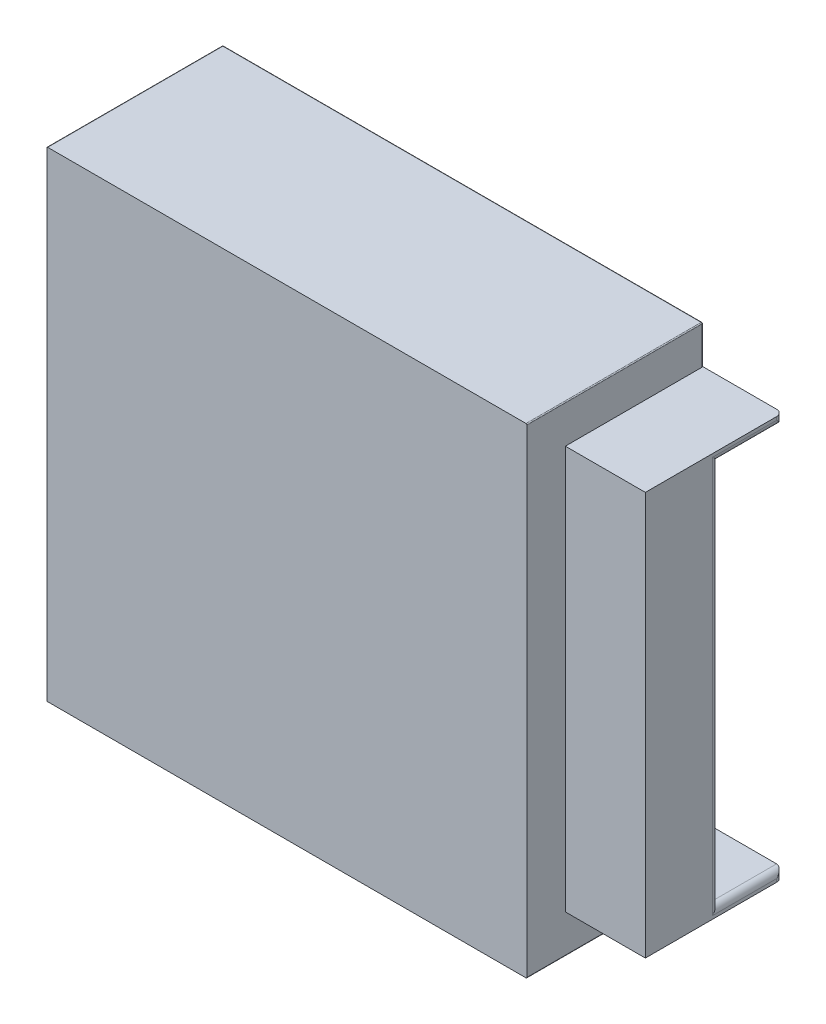
SolidWorks part; units mm, degrees
other "标注1"
sketch "草图9" plane through (0, -150, 0) normal (-0.0709, -0.2266, -0.9714) x (-0.9769, 0.2128, 0.0217)
ref_plane "前视基准面" through (0, 0, 0) normal (0, 0, 1) x (1, 0, 0)
ref_plane "上视基准面" through (0, 0, 0) normal (0, 1, 0) x (1, 0, 0)
ref_plane "右视基准面" through (0, 0, 0) normal (1, 0, 0) x (0, 0, -1)
sketch "草图1" plane through (0, 0, 0) normal (0, 0, 1) x (1, 0, 0)
  line L1 (0, 0) -> (150, 0)
  line L2 (0, 0) -> (0, -150)
  line L3 (0, -150) -> (150, -150)
  line L4 (150, 0) -> (150, -150)
  dimension "D1" = 150
  dimension "D2" = 150
extrude "凸台-拉伸2" add sketch "草图1" along normal blind 55
sketch "草图2" plane through (0, 0, 0) normal (0, 0, -1) x (-1, 0, 0)
  line L0 (0, -75) -> (-180.3535, -75) construction
  line L1 (-75, -150) -> (-75, 0) construction
  line L2 (-97, -55.8097) -> (-92.6, -55.8097) construction
  line L3 (-97, -53) -> (-53, -53)
  line L4 (0, -150) -> (0, 0)
  line L5 (0, 0) -> (-150, 0)
  line L6 (-150, 0) -> (-150, -150)
  line L7 (-150, -150) -> (0, -150)
  line L8 (0, -150) -> (0, 0)
  line L9 (0, 0) -> (-150, 0)
  line L10 (-150, 0) -> (-150, -150)
  line L11 (-150, -150) -> (0, -150)
  line L12 (-97, -53) -> (-97, -97)
  line L13 (-97, -97) -> (-53, -97)
  line L14 (-53, -53) -> (-53, -97)
  line L15 (-97, -53) -> (-53, -97) construction
  line L16 (-97, -97) -> (-53, -53) construction
  line L17 (-92.6, -53) -> (-97, -57.4)
  line L18 (-57.4, -53) -> (-53, -57.4)
  line L19 (-57.4, -97) -> (-53, -92.6)
  line L20 (-92.6, -97) -> (-97, -92.6)
  point P8 (-75, -75)
  dimension "D2" = 44
  dimension "D3" = 44
  dimension "D4" = 4.4
  dimension "D5" = 4.4
  dimension "D6" = 4.4
  dimension "D1" = 0
extrude "切除-拉伸1" cut sketch "草图2" against normal blind 52 contours L20 L13 L19 L14 L18 L3 L17 L12
sketch "草图3" plane through (0, 0, 0) normal (0, 0, -1) x (-1, 0, 0)
  line L0 (-53, -62.4) -> (-33, -62.4)
  line L1 (-53, -57.4) -> (-53, -92.6) construction
  line L2 (-33, -62.4) -> (-33, -87.6)
  line L3 (-33, -87.6) -> (-53, -87.6)
  line L4 (0, -150) -> (0, 0)
  line L5 (0, 0) -> (-150, 0)
  line L6 (-150, 0) -> (-150, -150)
  line L7 (-150, -150) -> (0, -150)
  line L8 (0, -150) -> (0, 0)
  line L9 (0, 0) -> (-150, 0)
  line L10 (-150, 0) -> (-150, -150)
  line L11 (-150, -150) -> (0, -150)
  line L12 (-53, -57.4) -> (-53, -92.6) construction
  line M16 (-53, -57.4) -> (-53, -92.6)
  dimension "D2" = 5
  dimension "D3" = 5
  dimension "D4" = 20
  dimension "D1" = 0
extrude "切除-拉伸2" cut sketch "草图3" against normal blind 52 contours L3 L2 L0 M16
sketch "草图4" plane through (0, 0, 0) normal (0, 0, -1) x (-1, 0, 0)
  line L4 (-90.6, -53) -> (-90.6, -29.3365)
  line L5 (-92.6, -53) -> (-57.4, -53) construction
  line L6 (-59.4, -53) -> (-59.4, -29.3365)
  line L7 (-59.4, -29.3365) -> (-90.6, -29.3365)
  line L8 (0, -150) -> (0, 0)
  line L9 (0, 0) -> (-150, 0)
  line L10 (-150, 0) -> (-150, -150)
  line L11 (-150, -150) -> (0, -150)
  line L12 (0, -150) -> (0, 0)
  line L13 (0, 0) -> (-150, 0)
  line L14 (-150, 0) -> (-150, -150)
  line L15 (-150, -150) -> (0, -150)
  line M17 (-92.6, -53) -> (-57.4, -53)
  dimension "D2" = 23.6635
  dimension "D3" = 2
  dimension "D4" = 2
  dimension "D1" = 0
extrude "切除-拉伸3" cut sketch "草图4" against normal blind 52 contours L6 L7 L4 M17
sketch "草图5" plane through (0, 0, 0) normal (0, 0, -1) x (-1, 0, 0)
  line L0 (-119.1643, -135) -> (-119.1643, -150) construction
  line L1 (-121.7237, 0) -> (-121.7237, -15) construction
  line L2 (-97, -60.4735) -> (-104, -60.4735) construction
  line L3 (-97, -57.4) -> (-97, -92.6) construction
  line L4 (0, -150) -> (0, 0)
  line L5 (0, 0) -> (-150, 0)
  line L6 (-150, 0) -> (-150, -150)
  line L7 (-150, -150) -> (0, -150)
  line L8 (0, -150) -> (0, 0)
  line L9 (0, 0) -> (-150, 0)
  line L10 (-150, 0) -> (-150, -150)
  line L11 (-150, -150) -> (0, -150)
  line L12 (-104, -60.4735) -> (-104, 3.8558) construction
  line L13 (-104, -60.4735) -> (-104, -150) construction
  line L14 (-121.7237, -15) -> (-88.1368, -15) construction
  line L16 (-104, -15) -> (-179, -15)
  line L17 (-104, -15) -> (-104, -135)
  line L18 (-104, -135) -> (-179, -135)
  line L19 (-179, -15) -> (-179, -135)
  dimension "D2" = 15
  dimension "D3" = 7
  dimension "D4" = 15
  dimension "D5" = 75
  dimension "D1" = 0
extrude "切除-拉伸4" cut sketch "草图5" against normal blind 40 contours L18 L17 L16 L10 | L16 L19 L18 L10
sketch "草图6" plane through (150, 0, 0) normal (1, 0, 0) x (0, 0, -1)
  line L1 (-40, -15) -> (-43, -15)
  line L2 (-40, -15) -> (-40, -135)
  line L3 (-40, -135) -> (-43, -135)
  line L4 (-43, -15) -> (-43, -135)
  line L5 (0, -135) -> (-43, -135)
  line L6 (0, -135) -> (0, -138)
  line L7 (0, -138) -> (-43, -138)
  line L8 (0, -135) -> (-40, -135)
  line L9 (-40, -135) -> (-40, -15)
  line L10 (-40, -15) -> (0, -15)
  line L11 (0, -15) -> (0, 0)
  line L12 (0, 0) -> (-55, 0)
  line L13 (-55, 0) -> (-55, -150)
  line L14 (-55, -150) -> (0, -150)
  line L15 (0, -150) -> (0, -135)
  line L16 (0, -135) -> (-40, -135)
  line L17 (-40, -135) -> (-40, -15)
  line L18 (-40, -15) -> (0, -15)
  line L19 (0, -15) -> (0, 0)
  line L20 (0, 0) -> (-55, 0)
  line L21 (-55, 0) -> (-55, -150)
  line L22 (-55, -150) -> (0, -150)
  line L23 (0, -150) -> (0, -135)
  line L24 (-43, -135) -> (-43, -138)
  line L25 (-43, -15) -> (0, -15)
  line L26 (-43, -15) -> (-43, -12)
  line L27 (-43, -12) -> (0, -12)
  line L28 (0, -15) -> (0, -12)
  line M10 (0, -135) -> (-40, -135)
  line M11 (-40, -135) -> (-40, -15)
  line M12 (-40, -15) -> (0, -15)
  line M13 (0, -15) -> (0, 0)
  line M17 (0, -150) -> (0, -135)
  dimension "D2" = 3
  dimension "D3" = 3
  dimension "D4" = 3
  dimension "D1" = 0
extrude "凸台-拉伸4" add sketch "草图6" along normal blind 25 contours L27 L26 L1 M12 M13 | L1 L4 L3 M11 | L3 L24 L7 M17 M10
sketch "草图7" plane through (0, 0, 40) normal (0, 0, -1) x (-1, 0, 0)
  line L1 (-175, -15) -> (-172, -15)
  line L2 (-175, -15) -> (-175, -135)
  line L3 (-175, -135) -> (-172, -135)
  line L4 (-104, -15) -> (-175, -15)
  line L5 (-175, -15) -> (-175, -135)
  line L6 (-175, -135) -> (-104, -135)
  line L7 (-104, -135) -> (-104, -15)
  line L8 (-104, -15) -> (-175, -15)
  line L9 (-175, -15) -> (-175, -135)
  line L10 (-175, -135) -> (-104, -135)
  line L11 (-104, -135) -> (-104, -15)
  line L12 (-172, -15) -> (-172, -135)
  line M7 (-104, -15) -> (-175, -15)
  line M8 (-175, -15) -> (-175, -135)
  line M9 (-175, -135) -> (-104, -135)
  dimension "D2" = 3
  dimension "D1" = 0
extrude "凸台-拉伸5" add sketch "草图7" along normal blind 20 contours L12 M7 M8 M9
sketch "草图8" plane through (0, 0, 0) normal (0, 0, -1) x (-1, 0, 0)
  line L1 (-104, -15) -> (-69, -15)
  line L2 (-104, -15) -> (-104, -29.3365)
  line L3 (-104, -29.3365) -> (-69, -29.3365)
  line L4 (-69, -15) -> (-69, -29.3365)
  line L6 (-59.4, -29.3365) -> (-90.6, -29.3365) construction
  line L8 (-150, -12) -> (-175, -12)
  line L9 (-175, -12) -> (-175, -15)
  line L10 (-175, -138) -> (-150, -138)
  line L11 (-150, -138) -> (-150, -150)
  line L12 (-150, -150) -> (0, -150)
  line L13 (0, -150) -> (0, 0)
  line L14 (0, 0) -> (-150, 0)
  line L15 (-150, 0) -> (-150, -12)
  line L16 (-150, -12) -> (-175, -12)
  line L17 (-175, -12) -> (-175, -15)
  line L18 (-175, -138) -> (-150, -138)
  line L19 (-150, -138) -> (-150, -150)
  line L20 (-150, -150) -> (0, -150)
  line L21 (0, -150) -> (0, 0)
  line L22 (0, 0) -> (-150, 0)
  line L23 (-150, 0) -> (-150, -12)
  line L35 (-104, -135) -> (-175, -135)
  line L36 (-104, -135) -> (-175, -135)
  line L37 (-175, -135) -> (-175, -138)
  line L38 (-175, -135) -> (-175, -138)
  line L39 (-175, -15) -> (-104, -15)
  line L40 (-175, -15) -> (-104, -15)
  line L41 (-104, -15) -> (-104, -135)
  line L42 (-104, -15) -> (-104, -135)
  line M16 (-104, -15) -> (-104, -135)
  line M17 (-90.6, -29.3365) -> (-59.4, -29.3365)
  dimension "D2" = 35
  dimension "D1" = 0
extrude "切除-拉伸6" cut sketch "草图8" against normal blind 30 contours L4 L1 L3 M16 M17
fillet "圆角1" radius 7 2 edges at (104, -22.1683, 30) (79.8, -29.3365, 30)
sketch "草图10" plane through (0, 0, 0) normal (0, 0, -1) x (-1, 0, 0)
  line L0 (-92.6, -97) -> (-92.6, -98.5) construction
  line L1 (-92.6, -98.5) -> (-12.6, -98.5) construction
  line L3 (-92.6, -98.5) -> (-12.6, -98.5)
  line L4 (-92.6, -98.5) -> (-92.6, -148.5)
  line L5 (-92.6, -148.5) -> (-12.6, -148.5)
  line L6 (-12.6, -98.5) -> (-12.6, -148.5)
  line L30 (-90.6, -53) -> (-90.6, -29.3365)
  line L31 (-90.6, -29.3365) -> (-104, -29.3365)
  line L32 (-104, -29.3365) -> (-104, -135)
  line L33 (-104, -135) -> (-175, -135)
  line L34 (-175, -135) -> (-175, -138)
  line L35 (-175, -138) -> (-150, -138)
  line L36 (-150, -138) -> (-150, -150)
  line L37 (-150, -150) -> (0, -150)
  line L38 (0, -150) -> (0, 0)
  line L39 (0, 0) -> (-150, 0)
  line L40 (-150, 0) -> (-150, -12)
  line L41 (-150, -12) -> (-175, -12)
  line L42 (-175, -12) -> (-175, -15)
  line L43 (-175, -15) -> (-69, -15)
  line L44 (-69, -15) -> (-69, -29.3365)
  line L45 (-69, -29.3365) -> (-59.4, -29.3365)
  line L46 (-59.4, -29.3365) -> (-59.4, -53)
  line L47 (-59.4, -53) -> (-57.4, -53)
  line L48 (-57.4, -53) -> (-53, -57.4)
  line L49 (-53, -57.4) -> (-53, -62.4)
  line L50 (-53, -62.4) -> (-33, -62.4)
  line L51 (-33, -62.4) -> (-33, -87.6)
  line L52 (-33, -87.6) -> (-53, -87.6)
  line L53 (-53, -87.6) -> (-53, -92.6)
  line L54 (-53, -92.6) -> (-57.4, -97)
  line L55 (-57.4, -97) -> (-92.6, -97)
  line L56 (-92.6, -97) -> (-97, -92.6)
  line L57 (-97, -92.6) -> (-97, -57.4)
  line L58 (-97, -57.4) -> (-92.6, -53)
  line L59 (-92.6, -53) -> (-90.6, -53)
  line L60 (-90.6, -53) -> (-90.6, -29.3365)
  line L61 (-90.6, -29.3365) -> (-104, -29.3365)
  line L62 (-104, -29.3365) -> (-104, -135)
  line L63 (-104, -135) -> (-175, -135)
  line L64 (-175, -135) -> (-175, -138)
  line L65 (-175, -138) -> (-150, -138)
  line L66 (-150, -138) -> (-150, -150)
  line L67 (-150, -150) -> (0, -150)
  line L68 (0, -150) -> (0, 0)
  line L69 (0, 0) -> (-150, 0)
  line L70 (-150, 0) -> (-150, -12)
  line L71 (-150, -12) -> (-175, -12)
  line L72 (-175, -12) -> (-175, -15)
  line L73 (-175, -15) -> (-69, -15)
  line L74 (-69, -15) -> (-69, -29.3365)
  line L75 (-69, -29.3365) -> (-59.4, -29.3365)
  line L76 (-59.4, -29.3365) -> (-59.4, -53)
  line L77 (-59.4, -53) -> (-57.4, -53)
  line L78 (-57.4, -53) -> (-53, -57.4)
  line L79 (-53, -57.4) -> (-53, -62.4)
  line L80 (-53, -62.4) -> (-33, -62.4)
  line L81 (-33, -62.4) -> (-33, -87.6)
  line L82 (-33, -87.6) -> (-53, -87.6)
  line L83 (-53, -87.6) -> (-53, -92.6)
  line L84 (-53, -92.6) -> (-57.4, -97)
  line L85 (-57.4, -97) -> (-92.6, -97)
  line L86 (-92.6, -97) -> (-97, -92.6)
  line L87 (-97, -92.6) -> (-97, -57.4)
  line L88 (-97, -57.4) -> (-92.6, -53)
  line L89 (-92.6, -53) -> (-90.6, -53)
  dimension "D2" = 1.5
  dimension "D3" = 80
  dimension "D4" = 50
  dimension "D5" = 80
  dimension "D1" = 0
extrude "切除-拉伸7" cut sketch "草图10" against normal blind 30 contours L4 L3 L6 L5
sketch "草图11" plane through (0, 0, 0) normal (0, 0, -1) x (-1, 0, 0)
  line L0 (-92.6, -98.5) -> (-92.6, -148.5) construction
  line L1 (-104, -105) -> (-92.6, -105)
  line L2 (-104, -105) -> (-104, -125)
  line L3 (-104, -125) -> (-92.6, -125)
  line L4 (-92.6, -105) -> (-92.6, -125)
  line L30 (-90.6, -53) -> (-90.6, -29.3365)
  line L31 (-90.6, -29.3365) -> (-104, -29.3365)
  line L32 (-104, -29.3365) -> (-104, -135)
  line L33 (-104, -135) -> (-175, -135)
  line L34 (-175, -135) -> (-175, -138)
  line L35 (-175, -138) -> (-150, -138)
  line L36 (-150, -138) -> (-150, -150)
  line L37 (-150, -150) -> (0, -150)
  line L38 (0, -150) -> (0, 0)
  line L39 (0, 0) -> (-150, 0)
  line L40 (-150, 0) -> (-150, -12)
  line L41 (-150, -12) -> (-175, -12)
  line L42 (-175, -12) -> (-175, -15)
  line L43 (-175, -15) -> (-69, -15)
  line L44 (-69, -15) -> (-69, -29.3365)
  line L45 (-69, -29.3365) -> (-59.4, -29.3365)
  line L46 (-59.4, -29.3365) -> (-59.4, -53)
  line L47 (-59.4, -53) -> (-57.4, -53)
  line L48 (-57.4, -53) -> (-53, -57.4)
  line L49 (-53, -57.4) -> (-53, -62.4)
  line L50 (-53, -62.4) -> (-33, -62.4)
  line L51 (-33, -62.4) -> (-33, -87.6)
  line L52 (-33, -87.6) -> (-53, -87.6)
  line L53 (-53, -87.6) -> (-53, -92.6)
  line L54 (-53, -92.6) -> (-57.4, -97)
  line L55 (-57.4, -97) -> (-92.6, -97)
  line L56 (-92.6, -97) -> (-97, -92.6)
  line L57 (-97, -92.6) -> (-97, -57.4)
  line L58 (-97, -57.4) -> (-92.6, -53)
  line L59 (-92.6, -53) -> (-90.6, -53)
  line L60 (-90.6, -53) -> (-90.6, -29.3365)
  line L61 (-90.6, -29.3365) -> (-104, -29.3365)
  line L62 (-104, -29.3365) -> (-104, -135)
  line L63 (-104, -135) -> (-175, -135)
  line L64 (-175, -135) -> (-175, -138)
  line L65 (-175, -138) -> (-150, -138)
  line L66 (-150, -138) -> (-150, -150)
  line L67 (-150, -150) -> (0, -150)
  line L68 (0, -150) -> (0, 0)
  line L69 (0, 0) -> (-150, 0)
  line L70 (-150, 0) -> (-150, -12)
  line L71 (-150, -12) -> (-175, -12)
  line L72 (-175, -12) -> (-175, -15)
  line L73 (-175, -15) -> (-69, -15)
  line L74 (-69, -15) -> (-69, -29.3365)
  line L75 (-69, -29.3365) -> (-59.4, -29.3365)
  line L76 (-59.4, -29.3365) -> (-59.4, -53)
  line L77 (-59.4, -53) -> (-57.4, -53)
  line L78 (-57.4, -53) -> (-53, -57.4)
  line L79 (-53, -57.4) -> (-53, -62.4)
  line L80 (-53, -62.4) -> (-33, -62.4)
  line L81 (-33, -62.4) -> (-33, -87.6)
  line L82 (-33, -87.6) -> (-53, -87.6)
  line L83 (-53, -87.6) -> (-53, -92.6)
  line L84 (-53, -92.6) -> (-57.4, -97)
  line L85 (-57.4, -97) -> (-92.6, -97)
  line L86 (-92.6, -97) -> (-97, -92.6)
  line L87 (-97, -92.6) -> (-97, -57.4)
  line L88 (-97, -57.4) -> (-92.6, -53)
  line L89 (-92.6, -53) -> (-90.6, -53)
  line M35 (-92.6, -148.5) -> (-92.6, -98.5)
  line M39 (-104, -29.3365) -> (-104, -135)
  dimension "D2" = 20
  dimension "D3" = 25
  dimension "D1" = 0
extrude "切除-拉伸8" cut sketch "草图11" against normal blind 30 contours L3 L1 M39 M35
fillet "圆角2" radius 5 1 edges at (104, -115, 30)
fillet "圆角3" radius 2 7 edges at (104, -29.3365, 18.5) (69, -29.3365, 18.5) (90.6, -29.3365, 15) (92.6, -105, 15) (92.6, -125, 15) (104, -125, 17.5) (104, -105, 17.5)
sketch "草图12" plane through (0, 0, 0) normal (0, 0, -1) x (-1, 0, 0)
  line L1 (-12.6, -115) -> (0, -115)
  line L2 (-12.6, -115) -> (-12.6, -135)
  line L3 (-12.6, -135) -> (0, -135)
  line L4 (0, -115) -> (0, -135)
  line L38 (-92.6, -29.3365) -> (-102, -29.3365)
  line L39 (-104, -31.3365) -> (-104, -103)
  line L40 (-102, -105) -> (-94.6, -105)
  line L41 (-92.6, -103) -> (-92.6, -98.5)
  line L42 (-92.6, -98.5) -> (-12.6, -98.5)
  line L43 (-12.6, -98.5) -> (-12.6, -148.5)
  line L44 (-12.6, -148.5) -> (-92.6, -148.5)
  line L45 (-92.6, -148.5) -> (-92.6, -127)
  line L46 (-94.6, -125) -> (-102, -125)
  line L47 (-104, -127) -> (-104, -135)
  line L48 (-104, -135) -> (-175, -135)
  line L49 (-175, -135) -> (-175, -138)
  line L50 (-175, -138) -> (-150, -138)
  line L51 (-150, -138) -> (-150, -150)
  line L52 (-150, -150) -> (0, -150)
  line L53 (0, -150) -> (0, 0)
  line L54 (0, 0) -> (-150, 0)
  line L55 (-150, 0) -> (-150, -12)
  line L56 (-150, -12) -> (-175, -12)
  line L57 (-175, -12) -> (-175, -15)
  line L58 (-175, -15) -> (-69, -15)
  line L59 (-69, -15) -> (-69, -27.3365)
  line L60 (-67, -29.3365) -> (-59.4, -29.3365)
  line L61 (-59.4, -29.3365) -> (-59.4, -53)
  line L62 (-59.4, -53) -> (-57.4, -53)
  line L63 (-57.4, -53) -> (-53, -57.4)
  line L64 (-53, -57.4) -> (-53, -62.4)
  line L65 (-53, -62.4) -> (-33, -62.4)
  line L66 (-33, -62.4) -> (-33, -87.6)
  line L67 (-33, -87.6) -> (-53, -87.6)
  line L68 (-53, -87.6) -> (-53, -92.6)
  line L69 (-53, -92.6) -> (-57.4, -97)
  line L70 (-57.4, -97) -> (-92.6, -97)
  line L71 (-92.6, -97) -> (-97, -92.6)
  line L72 (-97, -92.6) -> (-97, -57.4)
  line L73 (-97, -57.4) -> (-92.6, -53)
  line L74 (-92.6, -53) -> (-90.6, -53)
  line L75 (-90.6, -53) -> (-90.6, -31.3365)
  line L76 (-92.6, -29.3365) -> (-102, -29.3365)
  line L77 (-104, -31.3365) -> (-104, -103)
  line L78 (-102, -105) -> (-94.6, -105)
  line L79 (-92.6, -103) -> (-92.6, -98.5)
  line L80 (-92.6, -98.5) -> (-12.6, -98.5)
  line L81 (-12.6, -98.5) -> (-12.6, -148.5)
  line L82 (-12.6, -148.5) -> (-92.6, -148.5)
  line L83 (-92.6, -148.5) -> (-92.6, -127)
  line L84 (-94.6, -125) -> (-102, -125)
  line L85 (-104, -127) -> (-104, -135)
  line L86 (-104, -135) -> (-175, -135)
  line L87 (-175, -135) -> (-175, -138)
  line L88 (-175, -138) -> (-150, -138)
  line L89 (-150, -138) -> (-150, -150)
  line L90 (-150, -150) -> (0, -150)
  line L91 (0, -150) -> (0, 0)
  line L92 (0, 0) -> (-150, 0)
  line L93 (-150, 0) -> (-150, -12)
  line L94 (-150, -12) -> (-175, -12)
  line L95 (-175, -12) -> (-175, -15)
  line L96 (-175, -15) -> (-69, -15)
  line L97 (-69, -15) -> (-69, -27.3365)
  line L98 (-67, -29.3365) -> (-59.4, -29.3365)
  line L99 (-59.4, -29.3365) -> (-59.4, -53)
  line L100 (-59.4, -53) -> (-57.4, -53)
  line L101 (-57.4, -53) -> (-53, -57.4)
  line L102 (-53, -57.4) -> (-53, -62.4)
  line L103 (-53, -62.4) -> (-33, -62.4)
  line L104 (-33, -62.4) -> (-33, -87.6)
  line L105 (-33, -87.6) -> (-53, -87.6)
  line L106 (-53, -87.6) -> (-53, -92.6)
  line L107 (-53, -92.6) -> (-57.4, -97)
  line L108 (-57.4, -97) -> (-92.6, -97)
  line L109 (-92.6, -97) -> (-97, -92.6)
  line L110 (-97, -92.6) -> (-97, -57.4)
  line L111 (-97, -57.4) -> (-92.6, -53)
  line L112 (-92.6, -53) -> (-90.6, -53)
  line L113 (-90.6, -53) -> (-90.6, -31.3365)
  arc A7 (-102, -29.3365) -> (-104, -31.3365) centre (-102, -31.3365) ccw
  arc A8 (-104, -103) -> (-102, -105) centre (-102, -103) ccw
  arc A9 (-94.6, -105) -> (-92.6, -103) centre (-94.6, -103) ccw
  arc A10 (-92.6, -127) -> (-94.6, -125) centre (-94.6, -127) ccw
  arc A11 (-102, -125) -> (-104, -127) centre (-102, -127) ccw
  arc A12 (-69, -27.3365) -> (-67, -29.3365) centre (-67, -27.3365) ccw
  arc A13 (-90.6, -31.3365) -> (-92.6, -29.3365) centre (-92.6, -31.3365) ccw
  arc A14 (-102, -29.3365) -> (-104, -31.3365) centre (-102, -31.3365) ccw
  arc A15 (-104, -103) -> (-102, -105) centre (-102, -103) ccw
  arc A16 (-94.6, -105) -> (-92.6, -103) centre (-94.6, -103) ccw
  arc A17 (-92.6, -127) -> (-94.6, -125) centre (-94.6, -127) ccw
  arc A18 (-102, -125) -> (-104, -127) centre (-102, -127) ccw
  arc A19 (-69, -27.3365) -> (-67, -29.3365) centre (-67, -27.3365) ccw
  arc A20 (-90.6, -31.3365) -> (-92.6, -29.3365) centre (-92.6, -31.3365) ccw
  line M56 (-12.6, -98.5) -> (-12.6, -148.5)
  line M68 (0, -150) -> (0, 0)
  dimension "D2" = 20
  dimension "D3" = 15
  dimension "D1" = 0
extrude "切除-拉伸9" cut sketch "草图12" against normal blind 20 contours L3 L1 M56 M68
fillet "圆角4" radius 2 6 edges at (0, -125, 20) (0, -135, 10) (12.6, -135, 10) (12.6, -115, 10) (0, -115, 10) (12.6, -125, 20)
sketch "草图13" plane through (0, 0, 0) normal (0, 0, -1) x (-1, 0, 0)
  line L0 (-92.6, -53) -> (-100.8497, -53) construction
  line L1 (-97, -57.4) -> (-97, -50.7938) construction
  line L2 (-97, -75) -> (-44.1815, -75) construction
  line L3 (-75, -97) -> (-75, -54.3386) construction
  line L30 (-12.6, -98.5) -> (-12.6, -113)
  line L31 (-10.6, -115) -> (-2, -115)
  line L32 (0, -113) -> (0, 0)
  line L33 (0, 0) -> (-150, 0)
  line L34 (-150, 0) -> (-150, -12)
  line L35 (-150, -12) -> (-175, -12)
  line L36 (-175, -12) -> (-175, -15)
  line L37 (-175, -15) -> (-69, -15)
  line L38 (-69, -15) -> (-69, -27.3365)
  line L39 (-67, -29.3365) -> (-59.4, -29.3365)
  line L40 (-59.4, -29.3365) -> (-59.4, -53)
  line L41 (-59.4, -53) -> (-57.4, -53)
  line L42 (-57.4, -53) -> (-53, -57.4)
  line L43 (-53, -57.4) -> (-53, -62.4)
  line L44 (-53, -62.4) -> (-33, -62.4)
  line L45 (-33, -62.4) -> (-33, -87.6)
  line L46 (-33, -87.6) -> (-53, -87.6)
  line L47 (-53, -87.6) -> (-53, -92.6)
  line L48 (-53, -92.6) -> (-57.4, -97)
  line L49 (-57.4, -97) -> (-92.6, -97)
  line L50 (-92.6, -97) -> (-97, -92.6)
  line L51 (-97, -92.6) -> (-97, -57.4)
  line L52 (-97, -57.4) -> (-92.6, -53)
  line L53 (-92.6, -53) -> (-90.6, -53)
  line L54 (-90.6, -53) -> (-90.6, -31.3365)
  line L55 (-92.6, -29.3365) -> (-102, -29.3365)
  line L56 (-104, -31.3365) -> (-104, -103)
  line L57 (-102, -105) -> (-94.6, -105)
  line L58 (-92.6, -103) -> (-92.6, -98.5)
  line L59 (-92.6, -98.5) -> (-12.6, -98.5)
  line L60 (-12.6, -98.5) -> (-12.6, -113)
  line L61 (-10.6, -115) -> (-2, -115)
  line L62 (0, -113) -> (0, 0)
  line L63 (0, 0) -> (-150, 0)
  line L64 (-150, 0) -> (-150, -12)
  line L65 (-150, -12) -> (-175, -12)
  line L66 (-175, -12) -> (-175, -15)
  line L67 (-175, -15) -> (-69, -15)
  line L68 (-69, -15) -> (-69, -27.3365)
  line L69 (-67, -29.3365) -> (-59.4, -29.3365)
  line L70 (-59.4, -29.3365) -> (-59.4, -53)
  line L71 (-59.4, -53) -> (-57.4, -53)
  line L72 (-57.4, -53) -> (-53, -57.4)
  line L73 (-53, -57.4) -> (-53, -62.4)
  line L74 (-53, -62.4) -> (-33, -62.4)
  line L75 (-33, -62.4) -> (-33, -87.6)
  line L76 (-33, -87.6) -> (-53, -87.6)
  line L77 (-53, -87.6) -> (-53, -92.6)
  line L78 (-53, -92.6) -> (-57.4, -97)
  line L79 (-57.4, -97) -> (-92.6, -97)
  line L80 (-92.6, -97) -> (-97, -92.6)
  line L81 (-97, -92.6) -> (-97, -57.4)
  line L82 (-97, -57.4) -> (-92.6, -53)
  line L83 (-92.6, -53) -> (-90.6, -53)
  line L84 (-90.6, -53) -> (-90.6, -31.3365)
  line L85 (-92.6, -29.3365) -> (-102, -29.3365)
  line L86 (-104, -31.3365) -> (-104, -103)
  line L87 (-102, -105) -> (-94.6, -105)
  line L88 (-92.6, -103) -> (-92.6, -98.5)
  line L89 (-92.6, -98.5) -> (-12.6, -98.5)
  circle A0 centre (-97, -53) radius 0.75
  circle A1 centre (-97, -97) radius 0.75
  circle A2 centre (-53, -97) radius 0.75
  circle A3 centre (-53, -53) radius 0.75
  arc A7 (-12.6, -113) -> (-10.6, -115) centre (-10.6, -113) ccw
  arc A8 (-2, -115) -> (0, -113) centre (-2, -113) ccw
  arc A9 (-69, -27.3365) -> (-67, -29.3365) centre (-67, -27.3365) ccw
  arc A10 (-90.6, -31.3365) -> (-92.6, -29.3365) centre (-92.6, -31.3365) ccw
  arc A11 (-102, -29.3365) -> (-104, -31.3365) centre (-102, -31.3365) ccw
  arc A12 (-104, -103) -> (-102, -105) centre (-102, -103) ccw
  arc A13 (-94.6, -105) -> (-92.6, -103) centre (-94.6, -103) ccw
  arc A14 (-12.6, -113) -> (-10.6, -115) centre (-10.6, -113) ccw
  arc A15 (-2, -115) -> (0, -113) centre (-2, -113) ccw
  arc A16 (-69, -27.3365) -> (-67, -29.3365) centre (-67, -27.3365) ccw
  arc A17 (-90.6, -31.3365) -> (-92.6, -29.3365) centre (-92.6, -31.3365) ccw
  arc A18 (-102, -29.3365) -> (-104, -31.3365) centre (-102, -31.3365) ccw
  arc A19 (-104, -103) -> (-102, -105) centre (-102, -103) ccw
  arc A20 (-94.6, -105) -> (-92.6, -103) centre (-94.6, -103) ccw
  dimension "D2" = 1.5
  dimension "D1" = 0
extrude "切除-拉伸10" cut sketch "草图13" against normal blind 5 contours A0 | A3 | A2 | A1
fillet "圆角5" radius 2 5 edges at (175, -75, 20) (175, -135, 10) (175, -15, 10) (175, -13.5, 0) (175, -136.5, 0)
fillet "圆角6" radius 1 1 edges at (52.6, -148.5, 0)
fillet "圆角8" radius 0.3 18 edges at (12.6, -143.25, 0) (12.0142, -135.5858, 0) (6.3, -135, 0) (0.5858, -135.5858, 0) (12.6, -105.75, 0) (12.0142, -114.4142, 0) (6.3, -115, 0) (0.5858, -114.4142, 0) (150, 0, 27.5) (150, -6, 0) (150, -150, 27.5) (150, -144, 0) (0, -150, 27.5) (75, -150, 0) (0, -143.5, 0) (0, 0, 27.5) (0, -56.5, 0) (75, 0, 0)
